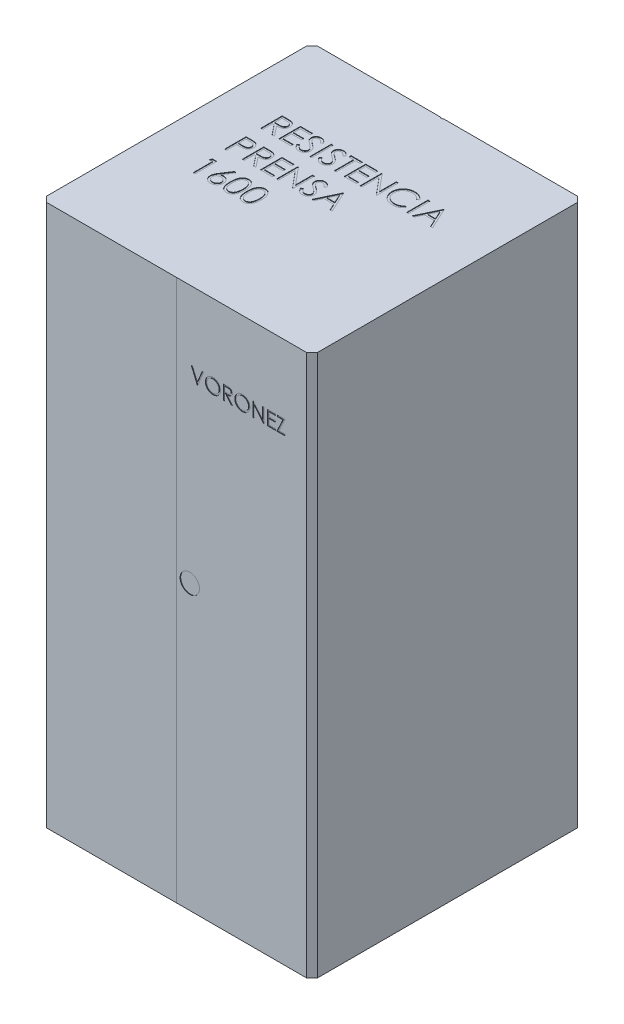
SolidWorks part; units mm, degrees
ref_plane "Alzado" through (0, 0, 0) normal (0, 0, 1) x (1, 0, 0)
ref_plane "Planta" through (0, 0, 0) normal (0, 1, 0) x (1, 0, 0)
ref_plane "Vista lateral" through (0, 0, 0) normal (1, 0, 0) x (0, 0, -1)
sketch "Croquis2" plane through (0, 0, 0) normal (0, 1, 0) x (1, 0, 0)
  line L1 (-500, 500) -> (500, 500)
  line L2 (-500, 500) -> (-500, -500)
  line L3 (-500, -500) -> (500, -500)
  line L4 (500, 500) -> (500, -500)
  line L5 (-500, 500) -> (500, -500) construction
  line L6 (-500, -500) -> (500, 500) construction
  point P0 (0, 0)
  dimension "D1" = 1000
  dimension "D2" = 1000
extrude "Saliente-Extruir1" add sketch "Croquis2" along normal blind 2000
sketch "Croquis3" plane through (0, 0, 500) normal (0, 0, 1) x (1, 0, 0)
  line L0 (0, 2000) -> (0, 0)
  line L1 (-500, 2000) -> (500, 2000) construction
extrude "Cortar-Extruir1" cut sketch "Croquis3" against normal blind 0.1 and the other way through all
chamfer "Chaflán1" distance 20 angle 45 4 edges at (-500, 1000, -500) (500, 1000, -500) (500, 1000, 499.9) (-500, 1000, 500)
sketch "Croquis4" plane through (0, 0, 499.9) normal (0, 0, 1) x (1, 0, 0)
  line L0 (51.5127, 1693.4534) -> (400.1741, 1693.4534) construction
  text T0 "VORONEZH" font "Century Gothic" height in points 200
extrude "Cortar-Extruir2" cut sketch "Croquis4" against normal blind 2
sketch "Croquis5" plane through (0, 2000, 0) normal (0, 1, 0) x (1, 0, 0)
  line L0 (-331.7004, 132.1901) -> (383.1401, 132.1901) construction
  text T0 "RESISTENCIA \r\nPRENSA\r\n1600" font "Century Gothic" height in points 300
extrude "Cortar-Extruir3" cut sketch "Croquis5" against normal blind 2
sketch "Croquis6" plane through (0, 0, 499.9) normal (0, 0, 1) x (1, 0, 0)
  circle A0 centre (48.7744, 1046.5574) radius 35.7484
  circle A1 centre (-84.2467, 1046.5574) radius 39.9063
extrude "Cortar-Extruir4" cut sketch "Croquis6" against normal blind 2
sketch "Croquis7" plane through (0, 0, -500) normal (0, 0, -1) x (-1, 0, 0)
  line L0 (-480, 0) -> (480, 0) construction
  line L1 (14.7688, 2000) -> (25.3943, 2000)
  line L2 (14.7688, 2000) -> (14.7688, 0)
  line L3 (14.7688, 0) -> (25.3943, 0)
  line L4 (25.3943, 2000) -> (25.3943, 0)
  line L5 (14.7688, 2000) -> (25.3943, 0) construction
  line L6 (14.7688, 0) -> (25.3943, 2000) construction
  point P0 (20.0816, 1000)
  point P7 (25.3943, 2000)
  point P9 (-6.6598, 0)
  point P10 (25.3943, 0)
  point P11 (25.3943, 0)
  point P12 (14.7688, 0)
extrude "Cortar-Extruir5" cut sketch "Croquis7" against normal blind 2
sketch "Croquis8" plane through (0, 0, -500) normal (0, 0, -1) x (-1, 0, 0)
  circle A0 centre (-74.6238, 990.9484) radius 27.5782
  circle A1 centre (101.963, 990.9484) radius 30.149
extrude "Cortar-Extruir6" cut sketch "Croquis8" against normal blind 2
